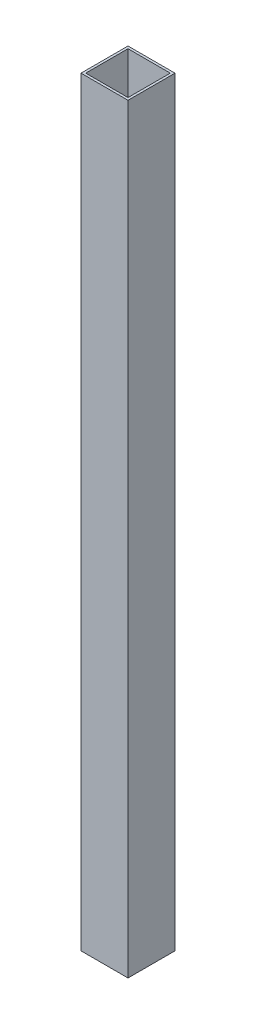
SolidWorks part; units mm, degrees
ref_plane "Front Plane" through (0, 0, 0) normal (0, 0, 1) x (1, 0, 0)
ref_plane "Top Plane" through (0, 0, 0) normal (0, 1, 0) x (1, 0, 0)
ref_plane "Right Plane" through (0, 0, 0) normal (1, 0, 0) x (0, 0, -1)
sketch "Sketch1" plane through (0, 0, 0) normal (0, 1, 0) x (1, 0, 0)
  line L1 (25.4, 25.4) -> (0, 25.4)
  line L2 (25.4, 25.4) -> (25.4, 0)
  line L3 (25.4, 0) -> (0, 0)
  line L4 (0, 25.4) -> (0, 0)
  line L5 (1.27, 1.27) -> (24.13, 1.27)
  line L6 (1.27, 1.27) -> (1.27, 24.13)
  line L7 (1.27, 24.13) -> (24.13, 24.13)
  line L8 (24.13, 1.27) -> (24.13, 24.13)
  line L9 (24.13, 24.13) -> (25.4, 24.13) construction
  line L10 (24.13, 24.13) -> (24.13, 25.4) construction
  line L11 (24.13, 25.4) -> (25.4, 25.4) construction
  line L12 (25.4, 24.13) -> (25.4, 25.4) construction
  line L13 (1.27, 1.27) -> (0, 1.27) construction
  line L14 (1.27, 1.27) -> (1.27, 0) construction
  line L15 (1.27, 0) -> (0, 0) construction
  line L16 (0, 1.27) -> (0, 0) construction
  dimension "D1" = 1.27
  dimension "D2" = 25.4
extrude "Boss-Extrude1" add sketch "Sketch1" along normal blind 410.8
